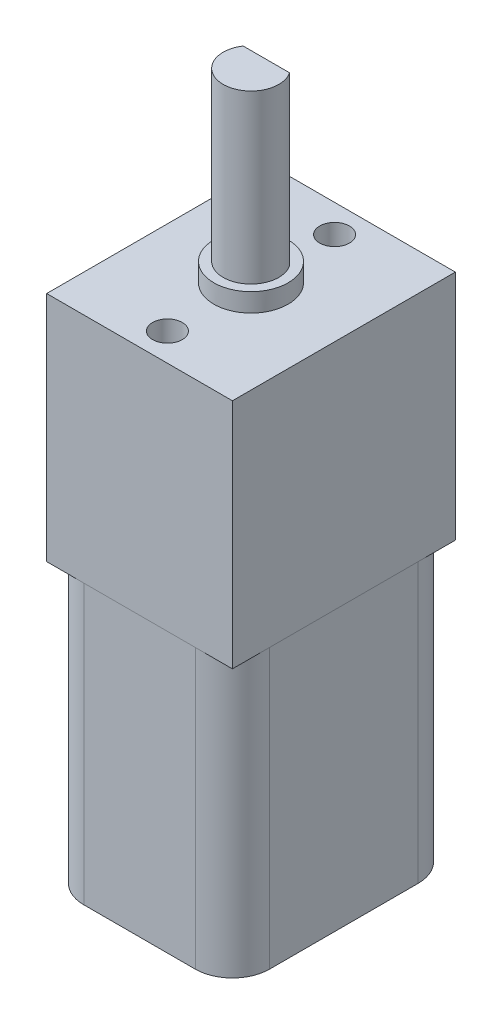
SolidWorks part; units mm, degrees
ref_plane "前视基准面" through (0, 0, 0) normal (0, 0, 1) x (1, 0, 0)
ref_plane "上视基准面" through (0, 0, 0) normal (0, 1, 0) x (1, 0, 0)
ref_plane "右视基准面" through (0, 0, 0) normal (1, 0, 0) x (0, 0, -1)
sketch "草图1" plane through (0, 0, 0) normal (0, 1, 0) x (1, 0, 0)
  line L1 (0, 0) -> (10, 0)
  line L2 (0, 0) -> (0, 12)
  line L3 (0, 12) -> (10, 12)
  line L4 (10, 0) -> (10, 12)
  dimension "D1" = 12
  dimension "D2" = 10
extrude "凸台-拉伸1" add sketch "草图1" along normal blind 27.5
sketch "草图2" plane through (0, 27.5, 0) normal (0, 1, 0) x (1, 0, 0)
  line L0 (0, 6) -> (10, 6) construction
  line L1 (0, 12) -> (0, 0) construction
  line L2 (10, 0) -> (10, 12) construction
  line L3 (3.75, 6.8292) -> (6.25, 6.8292)
  arc A0 (3.75, 6.8292) -> (6.25, 6.8292) centre (5, 6) ccw
  dimension "D1" = 3
  dimension "D2" = 2.5
extrude "凸台-拉伸2" add sketch "草图2" along normal blind 10
sketch "草图3" plane through (0, 27.5, 0) normal (0, 1, 0) x (1, 0, 0)
  circle A0 centre (5, 6) radius 2
  dimension "D1" = 4
extrude "凸台-拉伸3" add sketch "草图3" along normal blind 1
hole_wizard "Ø1.6 (1.6) 直径孔1" positions "草图4" profile "草图6" hole size "Ø1.6" standard "GB"
sketch "草图4" plane through (0, 27.5, 0) normal (0, 1, 0) x (1, 0, 0)
  line L0 (5, 12) -> (5, 0) construction
  line L1 (10, 12) -> (0, 12) construction
  line L2 (0, 0) -> (10, 0) construction
  line L3 (5, 6) -> (-3.8343, 6) construction
  point P9 (5, 10.5)
  point P11 (5, 1.5)
  dimension "D1" = 9
sketch "草图6" plane through (5, 27.5, -1.5) normal (1, 0, 0) x (0, 0, 1)
  line L0 (0, 0) -> (0, 2)
  line L1 (0, 2) -> (0.8, 2)
  line L2 (0.8, 2) -> (0.8, 0)
  line L5 (0.8, 0) -> (0, 0)
  line L10 (0, 2) -> (-0.8, 2) construction
  line L11 (0, -6.35) -> (0, 107.95) construction
  dimension "孔直径" = 1.6
  dimension "孔深度" = 2
  dimension "导头角度" = 180
ref_plane "基准面1" through (0, 15, 0) normal (0, -1, 0) x (-1, 0, 0)
sketch "草图7" plane through (0, 0, 0) normal (0, -1, 0) x (1, 0, 0)
  line L0 (0, -6) -> (10, -6) construction
  line L1 (0, -12) -> (0, 0) construction
  line L2 (10, 0) -> (10, -12) construction
  circle A0 centre (5, -6) radius 2.5
  dimension "D1" = 5
extrude "凸台-拉伸4" add sketch "草图7" along normal blind 2
split "分割1" trim tools "基准面1" bodies to split 110 resulting bodies 111 112
fillet "圆角1" radius 2 4 edges at (10, 7.5, -12) (0, 7.5, -12) (10, 7.5, 0) (0, 7.5, 0)
